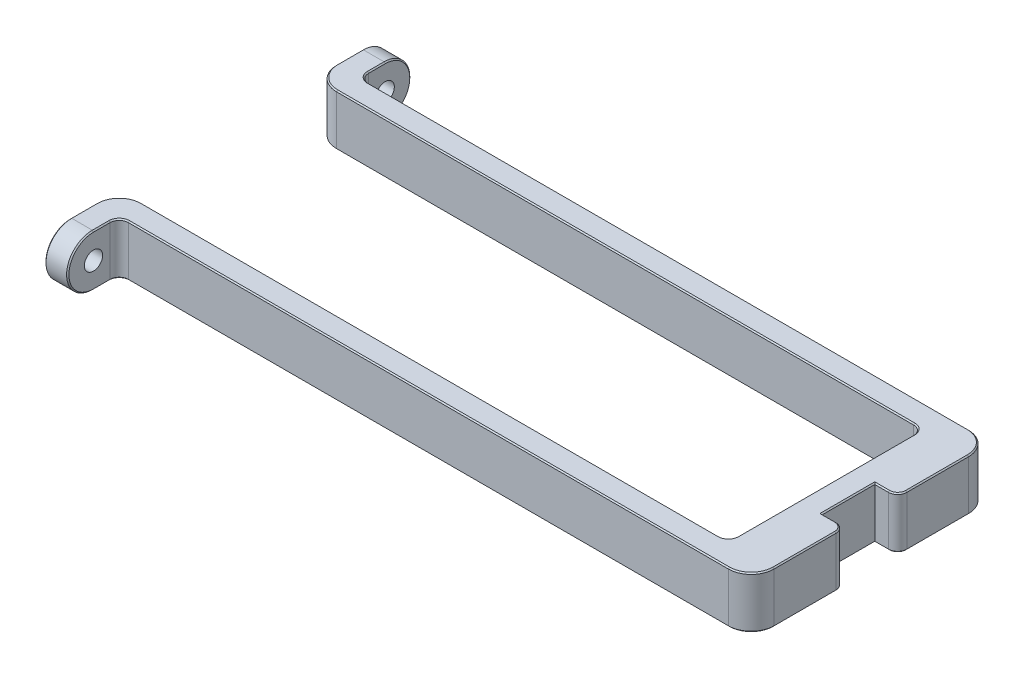
SolidWorks part; units mm, degrees
material "ABS"
ref_plane "前视基准面" through (0, 0, 0) normal (0, 0, 1) x (1, 0, 0)
ref_plane "上视基准面" through (0, 0, 0) normal (0, 1, 0) x (1, 0, 0)
ref_plane "右视基准面" through (0, 0, 0) normal (1, 0, 0) x (0, 0, -1)
sketch "草图1" plane through (0, 0, 0) normal (0, 1, 0) x (1, 0, 0)
  line L0 (0, 0) -> (0, 34)
  line L1 (0, 34) -> (106.5, 34)
  line L2 (106.5, 34) -> (106.5, 0)
  line L3 (106.5, 0) -> (0, 0)
  line L4 (110.5, -4) -> (0, -4)
  line L6 (0, 38) -> (110.5, 38)
  line L7 (110.5, 38) -> (110.5, -4)
  line L8 (0, 34) -> (0, 38)
  line L9 (0, 0) -> (0, -4)
  line L10 (-4, 38) -> (110.5, 38) construction
  line L11 (-4, -4) -> (-4, 38) construction
  line L12 (110.5, -4) -> (-4, -4) construction
  line L13 (110.5, 38) -> (114.5, 38)
  line L14 (114.5, 38) -> (114.5, 21.6)
  line L15 (114.5, 21.6) -> (110.5, 21.6)
  line L16 (110.5, 17) -> (0, 17) construction
  line L17 (114.5, 12.4) -> (110.5, 12.4)
  line L18 (114.5, -4) -> (114.5, 12.4)
  line L19 (110.5, -4) -> (114.5, -4)
  dimension "D1" = 106.5
  dimension "D2" = 34
  dimension "D4" = 9.2
  dimension "D5" = 4
  dimension "D3" = 4
extrude "凸台-拉伸1" add sketch "草图1" along normal blind 9 contours L3 L9 L4 L7 L6 L8 L1 L2 | L15 L14 L13 L7 | L7 L19 L18 L17
sketch "草图2" plane through (0, 0, 0) normal (-1, 0, 0) x (0, 0, 1)
  line L0 (0, 4.5) -> (4, 4.5) construction
  line L1 (0, 9) -> (0, 0) construction
  line L2 (4, 9) -> (4, 0) construction
  line L3 (8.5, 4.5) -> (4, 4.5) construction
  line L4 (4, 9) -> (8.5, 9)
  line L5 (8.5, 0) -> (4, 0)
  line L7 (0, 9) -> (4, 9) construction
  line L9 (-17, 0) -> (-17, 9) construction
  line L10 (-34, 0) -> (0, 0) construction
  line L11 (-34, 9) -> (0, 9) construction
  line L12 (-42.5, 4.5) -> (-38, 4.5) construction
  line L13 (-42.5, 0) -> (-38, 0)
  line L14 (-38, 9) -> (-42.5, 9)
  line L15 (-38, 9) -> (-38, 0)
  line L16 (4, 9) -> (4, 0)
  circle A0 centre (8.5, 4.5) radius 4.5
  circle A1 centre (8.5, 4.5) radius 1.6
  circle A2 centre (-42.5, 4.5) radius 1.6
  circle A3 centre (-42.5, 4.5) radius 4.5
  line M8 (4, 0) -> (4, 9)
  dimension "D1" = 9
  dimension "D2" = 3.2
extrude "凸台-拉伸2" add sketch "草图2" against normal blind 4 contours A3 A2 | L14 A3 L15 | L15 A3 L13 | A0 A1 | A0 L4 L16 | A0 L5 M8
fillet "圆角1" radius 4 4 edges at (0, 4.5, 0) (0, 4.5, -34) (114.5, 4.5, -38) (114.5, 4.5, 4)
fillet "圆角2" radius 1.6 6 edges at (4, 4.5, 4) (4, 4.5, -38) (106.5, 4.5, 0) (106.5, 4.5, -34) (114.5, 4.5, -12.4) (114.5, 4.5, -21.6)
chamfer "倒角1" distance 0.2 angle 45 52 edges at (0, 0, -40.25) (1.1716, 0, -35.1716) (54.45, 0, -34) (106.0314, 0, -33.5314) (106.5, 0, -17) (106.0314, 0, -0.4686) (54.45, 0, 0) (1.1716, 0, 1.1716) (0, 0, 6.25) (4, 0, -41.05) (4.4686, 0, -38.4686) (58.05, 0, -38) (113.3284, 0, -36.8284) (114.5, 0, -28.6) (114.0314, 0, -22.0686) (111.7, 0, -21.6) (110.5, 0, -17) (4, 0, 7.05) (4.4686, 0, 4.4686) (58.05, 0, 4) (113.3284, 0, 2.8284) (114.5, 0, -5.4) (114.0314, 0, -11.9314) (111.7, 0, -12.4) (0, 4.5, 13) (4, 4.5, 13) (0, 4.5, -47) (4, 4.5, -47) (0, 9, 6.25) (1.1716, 9, 1.1716) (54.45, 9, 0) (106.0314, 9, -0.4686) (106.5, 9, -17) (106.0314, 9, -33.5314) (54.45, 9, -34) (1.1716, 9, -35.1716) (0, 9, -40.25) (4, 9, 7.05) (4.4686, 9, 4.4686) (58.05, 9, 4) (113.3284, 9, 2.8284) (4, 9, -41.05) (4.4686, 9, -38.4686) (58.05, 9, -38) (113.3284, 9, -36.8284) (114.5, 9, -28.6) (114.0314, 9, -22.0686) (111.7, 9, -21.6) (110.5, 9, -17) (111.7, 9, -12.4) (114.0314, 9, -11.9314) (114.5, 9, -5.4)
